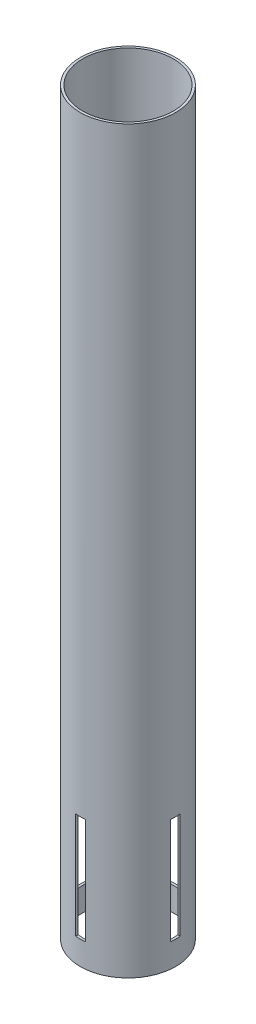
SolidWorks part; units mm, degrees
ref_plane "Front Plane" through (0, 0, 0) normal (0, 0, 1) x (1, 0, 0)
ref_plane "Top Plane" through (0, 0, 0) normal (0, 1, 0) x (1, 0, 0)
ref_plane "Right Plane" through (0, 0, 0) normal (1, 0, 0) x (0, 0, -1)
sketch "Sketch1" plane through (0, 0, 0) normal (0, 1, 0) x (1, 0, 0)
  circle A0 centre (0, 0) radius 50.8
  circle A1 centre (0, 0) radius 48.26
  dimension "D1" = 101.6
  dimension "D2" = 2.54
extrude "Boss-Extrude1" add sketch "Sketch1" along normal blind 787.4
sketch "Sketch2" plane through (0, 0, 0) normal (0, 0, 1) x (1, 0, 0)
  line L0 (-50.8, 0) -> (50.8, 0) construction
  line L1 (-5.08, 25.4) -> (5.08, 25.4)
  line L2 (-5.08, 25.4) -> (-5.08, 138.176)
  line L3 (-5.08, 138.176) -> (5.08, 138.176)
  line L4 (5.08, 25.4) -> (5.08, 138.176)
  point P4 (0, 138.176)
  dimension "D1" = 112.776
  dimension "D2" = 10.16
  dimension "D3" = 25.4
extrude "Cut-Extrude1" cut sketch "Sketch2" against normal through all both and the other way through all
sketch "Sketch3" plane through (0, 0, 0) normal (1, 0, 0) x (0, 0, -1)
  line L1 (-5.08, 138.176) -> (5.08, 138.176)
  line L2 (-5.08, 138.176) -> (-5.08, 25.4)
  line L3 (-5.08, 25.4) -> (5.08, 25.4)
  line L4 (5.08, 138.176) -> (5.08, 25.4)
  line L5 (-50.8, 0) -> (50.8, 0) construction
  point P4 (0, 138.176)
  dimension "D1" = 112.776
  dimension "D2" = 10.16
  dimension "D3" = 25.4
extrude "Cut-Extrude2" cut sketch "Sketch3" against normal through all both and the other way through all
